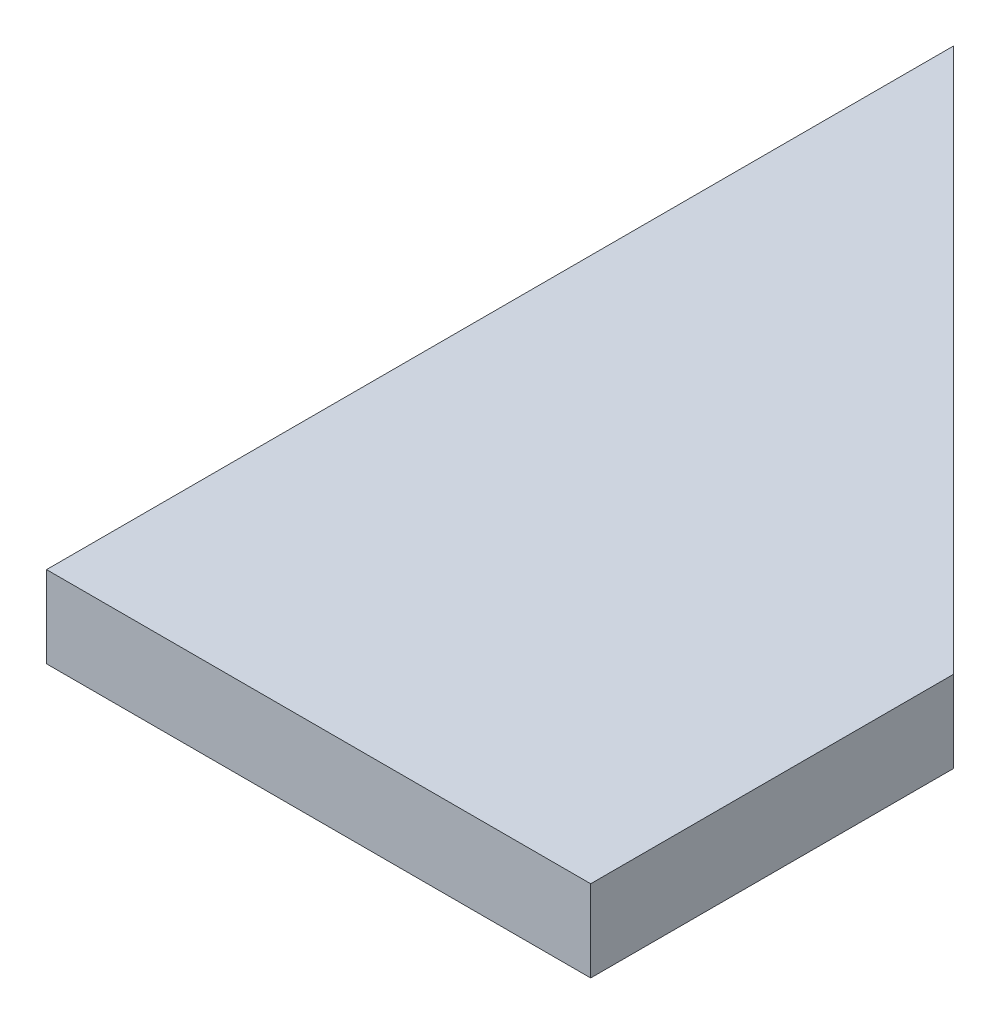
SolidWorks part; units mm, degrees
material "Perspex (TM) GS Acrylic Cast Sheet"
ref_plane "Front Plane" through (0, 0, 0) normal (0, 0, 1) x (1, 0, 0)
ref_plane "Top Plane" through (0, 0, 0) normal (0, 1, 0) x (1, 0, 0)
ref_plane "Right Plane" through (0, 0, 0) normal (1, 0, 0) x (0, 0, -1)
sketch "Sketch2" plane through (0, 0, 0) normal (0, 1, 0) x (1, 0, 0)
  line L0 (0, 0) -> (30, 0)
  line L1 (0, 0) -> (0, 50)
  line L2 (30, 0) -> (30, 20)
  line L3 (0, 50) -> (30, 20)
  dimension "D1" = 45
  dimension "D2" = 90
  dimension "D3" = 90
  dimension "D4" = 30
  dimension "D5" = 50
extrude "Boss-Extrude1" add sketch "Sketch2" along normal blind 4.5
